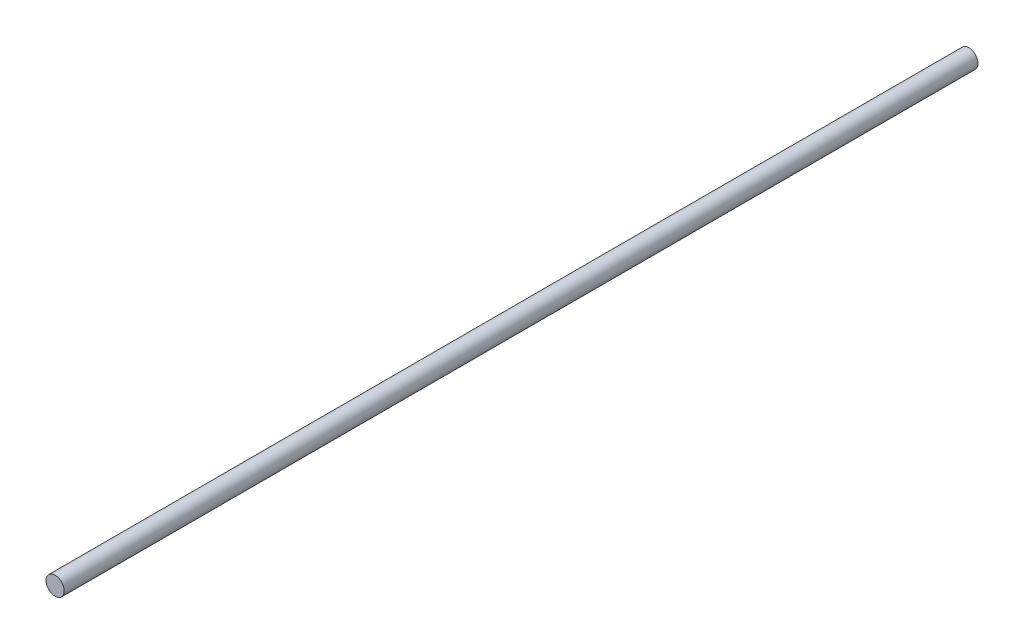
SolidWorks part; units mm, degrees
ref_plane "Front Plane" through (0, 0, 0) normal (0, 0, 1) x (1, 0, 0)
ref_plane "Top Plane" through (0, 0, 0) normal (0, 1, 0) x (1, 0, 0)
ref_plane "Right Plane" through (0, 0, 0) normal (1, 0, 0) x (0, 0, -1)
sketch "Sketch1" plane through (0, 0, 0) normal (0, 0, 1) x (1, 0, 0)
  circle A0 centre (0, 0) radius 15
extrude "Boss-Extrude1" add sketch "Sketch1" along normal blind 1500
